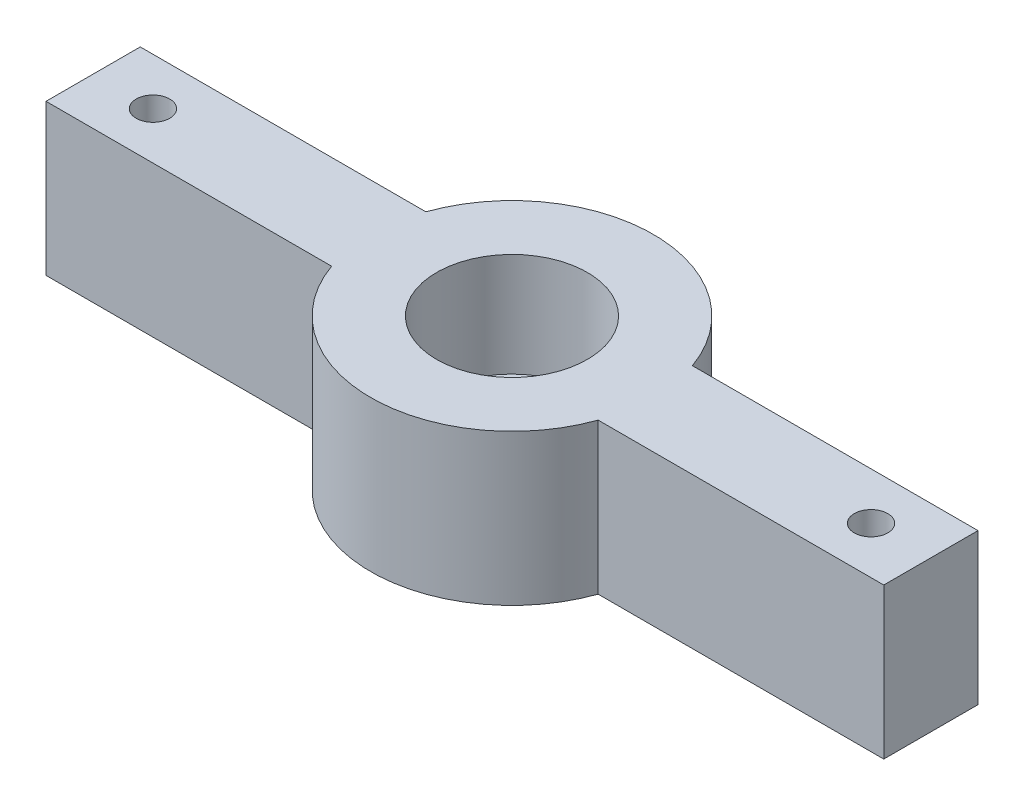
SolidWorks part; units mm, degrees
ref_plane "Front Plane" through (0, 0, 0) normal (0, 0, 1) x (1, 0, 0)
ref_plane "Top Plane" through (0, 0, 0) normal (0, 1, 0) x (1, 0, 0)
ref_plane "Right Plane" through (0, 0, 0) normal (1, 0, 0) x (0, 0, -1)
sketch "Sketch1" plane through (0, 0, 0) normal (0, 1, 0) x (1, 0, 0)
  line L0 (-22.225, 2.5) -> (-22.225, -2.5)
  line L1 (-22.225, -2.5) -> (-7.0711, -2.5)
  line L2 (22.225, -2.5) -> (22.225, 2.5)
  line L3 (22.225, 2.5) -> (7.0711, 2.5)
  line L4 (-22.225, 0) -> (22.225, 0) construction
  line L5 (-7.0711, 2.5) -> (-22.225, 2.5)
  line L6 (7.0711, -2.5) -> (22.225, -2.5)
  line L7 (0, 0) -> (0, 16.7972) construction
  arc A0 (-7.0711, -2.5) -> (7.0711, -2.5) centre (0, 0) ccw
  arc A1 (7.0711, 2.5) -> (-7.0711, 2.5) centre (0, 0) ccw
  circle A2 centre (-19.05, 0) radius 0.889
  circle A3 centre (0, 0) radius 1.875
  circle A4 centre (19.05, 0) radius 0.889
  dimension "D3" = 15
  dimension "D5" = 3.75
  dimension "D1" = 5
  dimension "D2" = 44.45
  dimension "D4" = 19.05
extrude "Boss-Extrude1" add sketch "Sketch1" along normal blind 8
sketch "Sketch2" plane through (0, 8, 0) normal (0, 1, 0) x (1, 0, 0)
  circle A0 centre (0, 0) radius 4
  dimension "D1" = 8
extrude "Cut-Extrude1" cut sketch "Sketch2" against normal blind 5.5
